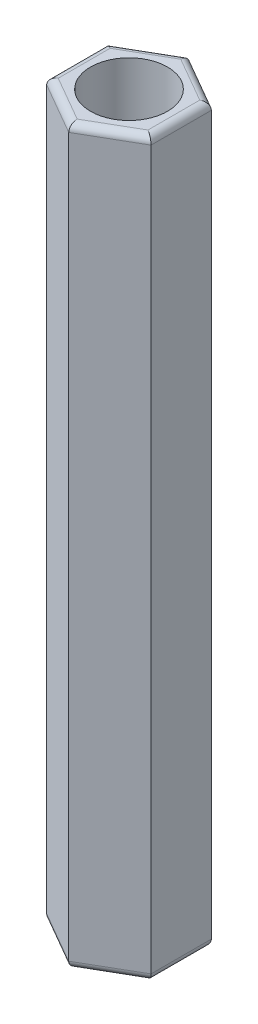
SolidWorks part; units mm, degrees
ref_plane "Front Plane" through (0, 0, 0) normal (0, 0, 1) x (1, 0, 0)
ref_plane "Top Plane" through (0, 0, 0) normal (0, 1, 0) x (1, 0, 0)
ref_plane "Right Plane" through (0, 0, 0) normal (1, 0, 0) x (0, 0, -1)
sketch "Sketch1" plane through (0, 0, 0) normal (0, 1, 0) x (1, 0, 0)
  line L1 (1.425, 0.8227) -> (0, 1.6454)
  line L2 (0, 1.6454) -> (-1.425, 0.8227)
  line L3 (-1.425, 0.8227) -> (-1.425, -0.8227)
  line L4 (-1.425, -0.8227) -> (0, -1.6454)
  line L5 (0, -1.6454) -> (1.425, -0.8227)
  line L6 (1.425, -0.8227) -> (1.425, 0.8227)
  circle A0 centre (0, 0) radius 1.425 construction
  circle A1 centre (0, 0) radius 1.05
  dimension "D2" = 2.1
  dimension "D1" = 2.85
extrude "Boss-Extrude1" add sketch "Sketch1" along normal blind 20
fillet "Fillet1" radius 0.2 12 edges at (0.7125, 0, -1.2341) (1.425, 0, 0) (0.7125, 0, 1.2341) (-0.7125, 0, 1.2341) (-0.7125, 0, -1.2341) (-1.425, 0, 0) (-1.425, 20, 0) (-0.7125, 20, -1.2341) (0.7125, 20, -1.2341) (1.425, 20, 0) (0.7125, 20, 1.2341) (-0.7125, 20, 1.2341)
